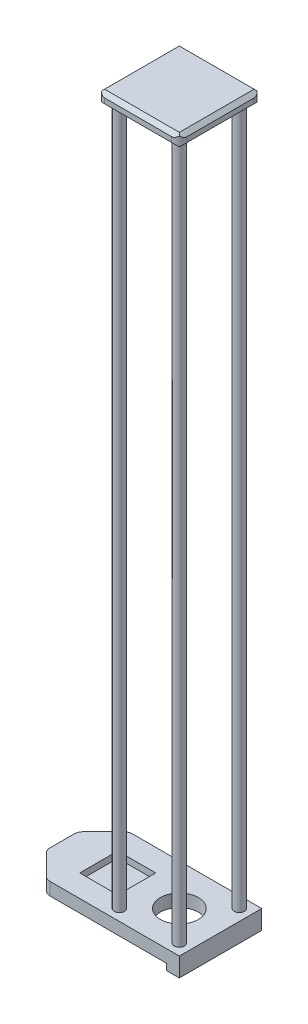
SolidWorks part; units mm, degrees
ref_plane "Front Plane" through (0, 0, 0) normal (0, 0, 1) x (1, 0, 0)
ref_plane "Top Plane" through (0, 0, 0) normal (0, 1, 0) x (1, 0, 0)
ref_plane "Right Plane" through (0, 0, 0) normal (1, 0, 0) x (0, 0, -1)
sketch "Sketch1" plane through (0, 0, 0) normal (0, 1, 0) x (1, 0, 0)
  line L1 (-65, -65) -> (65, -65)
  line L2 (-65, -65) -> (-65, 65)
  line L3 (-65, 65) -> (65, 65)
  line L4 (65, -65) -> (65, 65)
  line L5 (-65, -65) -> (65, 65) construction
  line L6 (-65, 65) -> (65, -65) construction
  point P0 (0, 0)
extrude "Boss-Extrude2" add sketch "Sketch1" along normal blind 20
sketch "Sketch2" plane through (0, 20, 0) normal (0, 1, 0) x (1, 0, 0)
  circle A0 centre (0, 0) radius 40
extrude "Cut-Extrude1" cut sketch "Sketch2" against normal through all
sketch "Sketch3" plane through (0, 20, 0) normal (0, 1, 0) x (1, 0, 0)
  circle A0 centre (0, 0) radius 30
  circle A1 centre (0, 0) radius 40
extrude "Boss-Extrude3" add sketch "Sketch3" along normal blind 20 separate body
sketch "Sketch4" plane through (0, 0, 65) normal (0, 0, 1) x (1, 0, 0)
  line L1 (-65, 20) -> (60.4506, 20)
  line L2 (-65, 20) -> (-65, 51.4651)
  line L3 (-65, 51.4651) -> (60.4506, 51.4651)
  line L4 (60.4506, 20) -> (60.4506, 51.4651)
extrude "Cut-Extrude2" cut sketch "Sketch4" against normal through all
sketch "Sketch5" plane through (0, 0, 0) normal (0, -1, 0) x (1, 0, 0)
  circle A0 centre (0, 0) radius 30
  circle A1 centre (0, 0) radius 40
extrude "Boss-Extrude4" add sketch "Sketch5" against normal blind 20
sketch "Sketch6" plane through (0, 20, 0) normal (0, 1, 0) x (1, 0, 0)
  line L0 (0, 65) -> (0, -65) construction
  line L1 (65, 65) -> (-65, 65) construction
  line L2 (-65, -65) -> (65, -65) construction
  line L3 (-65, 0) -> (65, 0) construction
  line L4 (-65, 65) -> (-65, -65) construction
  line L5 (65, -65) -> (65, 65) construction
  circle A0 centre (-47.3223, 47.3223) radius 8
  circle A1 centre (47.3223, 47.3223) radius 8
  circle A2 centre (47.3223, -47.3223) radius 8
  circle A3 centre (-47.3223, -47.3223) radius 8
extrude "Boss-Extrude5" add sketch "Sketch6" along normal blind 1100
sketch "Sketch7" plane through (0, 1120, 0) normal (0, 1, 0) x (1, 0, 0)
  line L1 (-65, 65) -> (65, 65)
  line L2 (-65, 65) -> (-65, -65)
  line L3 (-65, -65) -> (65, -65)
  line L4 (65, 65) -> (65, -65)
extrude "Boss-Extrude6" add sketch "Sketch7" along normal blind 20
sketch "Sketch8" plane through (0, 0, 0) normal (0, -1, 0) x (1, 0, 0)
  line L0 (65, -65) -> (-65, -65) construction
  line L1 (65, 65) -> (45, 65)
  line L2 (65, 65) -> (65, -65)
  line L3 (65, -65) -> (45, -65)
  line L4 (45, 65) -> (45, -65)
extrude "Boss-Extrude7" add sketch "Sketch8" along normal blind 10
sketch "Sketch9" plane through (-65, 0, 0) normal (-1, 0, 0) x (0, 0, 1)
  line L1 (-65, 20) -> (65, 20)
  line L2 (-65, 20) -> (-65, 0)
  line L3 (-65, 0) -> (65, 0)
  line L4 (65, 20) -> (65, 0)
extrude "Boss-Extrude8" add sketch "Sketch9" along normal blind 120
sketch "Sketch10" plane through (0, 0, 0) normal (0, -1, 0) x (1, 0, 0)
  line L0 (0, 0) -> (-48.62, 0) construction
  circle A0 centre (-48.62, 0) radius 5
extrude "Boss-Extrude9" add sketch "Sketch10" along normal blind 10
sketch "Sketch11" plane through (0, 0, 0) normal (0, -1, 0) x (1, 0, 0)
  line L0 (-48.62, 0) -> (-97.24, 0) construction
  circle A0 centre (-97.24, 0) radius 5
extrude "Cut-Extrude3" cut sketch "Sketch11" against normal through all
sketch "Sketch12" plane through (0, 20, 0) normal (0, 1, 0) x (1, 0, 0)
  line L1 (-127.24, -30) -> (-67.24, -30)
  line L2 (-127.24, -30) -> (-127.24, 30)
  line L3 (-127.24, 30) -> (-67.24, 30)
  line L4 (-67.24, -30) -> (-67.24, 30)
  line L5 (-127.24, -30) -> (-67.24, 30) construction
  line L6 (-127.24, 30) -> (-67.24, -30) construction
  point P0 (-97.24, 0)
extrude "Cut-Extrude4" cut sketch "Sketch12" against normal blind 10
chamfer "Chamfer1" distance 40 angle 45 2 edges at (-185, 10, -65) (-185, 10, 65)
fillet "Fillet1" radius 15 4 edges at (-145, 10, 65) (-185, 10, 25) (-185, 10, -25) (-145, 10, -65)
sketch "Sketch13" plane through (0, 0, 0) normal (0, -1, 0) x (1, 0, 0)
  line L0 (-142.9025, -15.7273) -> (-142.9025, 15.7273) construction
  line L1 (-157.9025, -15.7273) -> (-157.9025, 15.7273)
  line L2 (-127.9025, -15.7273) -> (-127.9025, 15.7273)
  arc A0 (-157.9025, -15.7273) -> (-127.9025, -15.7273) centre (-142.9025, -15.7273) ccw
  arc A1 (-127.9025, 15.7273) -> (-157.9025, 15.7273) centre (-142.9025, 15.7273) ccw
  point P2 (-142.9025, 0)
extrude "Boss-Extrude10" add sketch "Sketch13" along normal blind 10
chamfer "Chamfer2" distance 6 angle 45 8 edges at (0, 1140, -65) (65, 1140, 0) (0, 1140, 65) (-65, 1140, 0) (0, 1120, -65) (65, 1120, 0) (0, 1120, 65) (-65, 1120, 0)
fillet "Fillet2" radius 12 4 edges at (-65, 1130, -65) (65, 1130, -65) (65, 1130, 65) (-65, 1130, 65)
